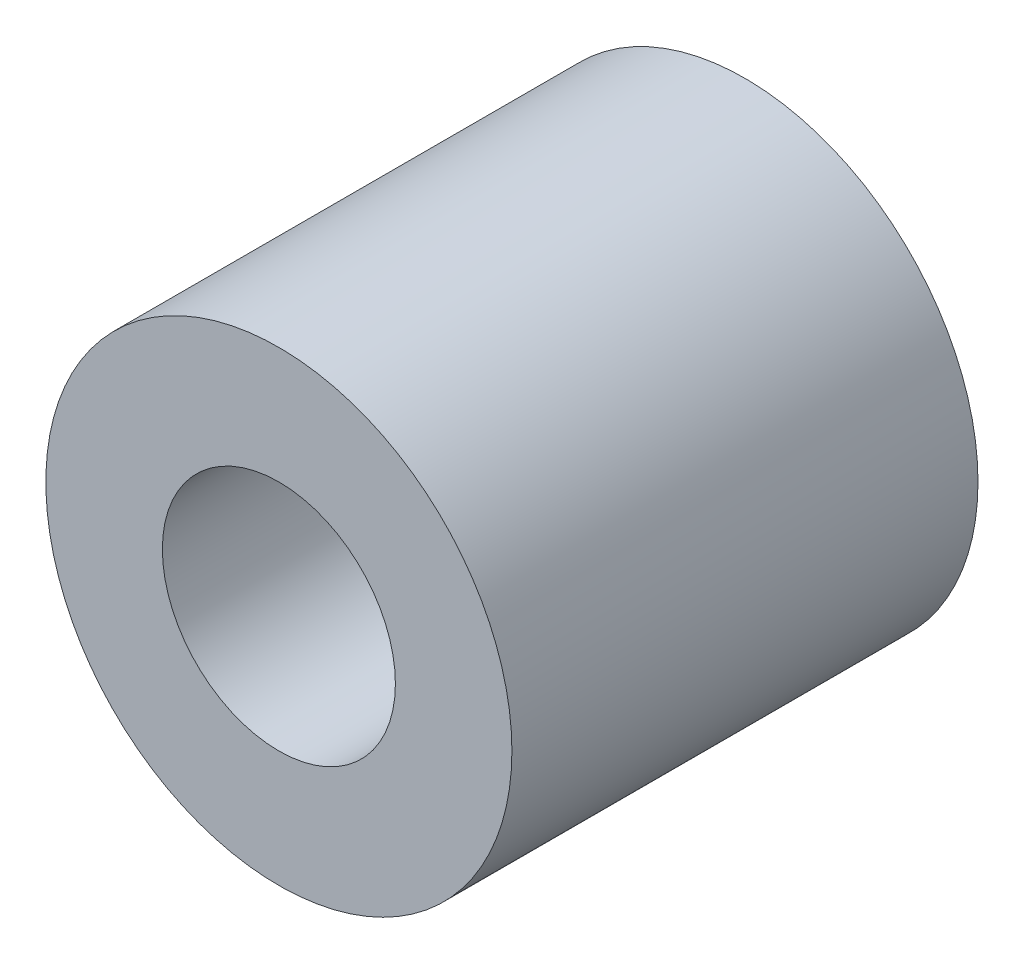
SolidWorks part; units mm, degrees
ref_plane "Front Plane" through (0, 0, 0) normal (0, 0, 1) x (1, 0, 0)
ref_plane "Top Plane" through (0, 0, 0) normal (0, 1, 0) x (1, 0, 0)
ref_plane "Right Plane" through (0, 0, 0) normal (1, 0, 0) x (0, 0, -1)
sketch "Sketch2" plane through (0, 0, 0) normal (0, 0, 1) x (1, 0, 0)
  circle A0 centre (0, 0) radius 5
  dimension "D1" = 10
extrude "Boss-Extrude1" add sketch "Sketch2" along normal blind 10
sketch "Sketch3" plane through (0, 0, 10) normal (0, 0, 1) x (1, 0, 0)
  circle A0 centre (0, 0) radius 2.5
  dimension "D1" = 5
extrude "Cut-Extrude1" cut sketch "Sketch3" against normal up to next
